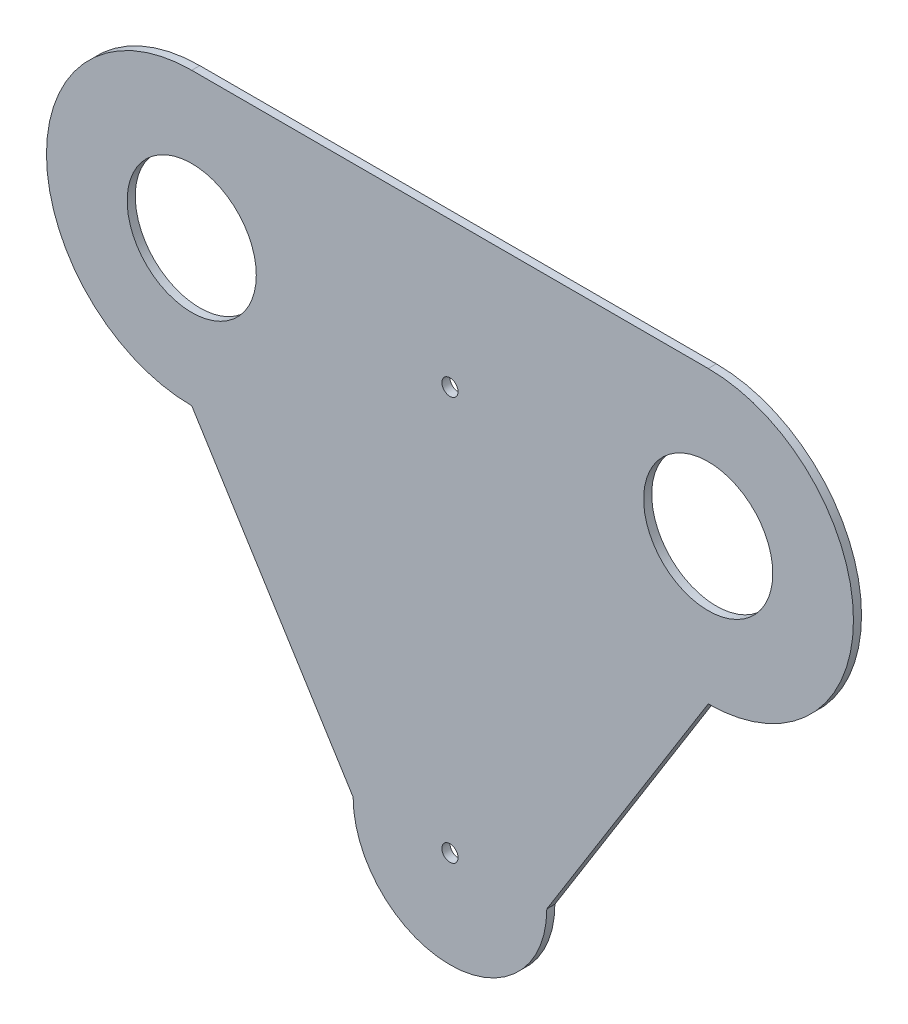
SolidWorks part; units mm, degrees
ref_plane "Front Plane" through (0, 0, 0) normal (0, 0, 1) x (1, 0, 0)
ref_plane "Top Plane" through (0, 0, 0) normal (0, 1, 0) x (1, 0, 0)
ref_plane "Right Plane" through (0, 0, 0) normal (1, 0, 0) x (0, 0, -1)
sketch "Sketch1" plane through (0, 0, 0) normal (0, 0, 1) x (1, 0, 0)
  line L0 (-80, 0) -> (80, 0)
  line L1 (0, 0) -> (0, -125)
  line L2 (-80, 45) -> (80, 45)
  line L3 (-80, -45) -> (-30, -125)
  line L4 (30, -125) -> (80, -45)
  line L5 (-30, -125) -> (30, -125)
  line L6 (-80, -45) -> (80, -45)
  circle A0 centre (-80, 0) radius 20
  circle A1 centre (80, 0) radius 20
  circle A2 centre (0, 0) radius 2.5
  circle A3 centre (0, -125) radius 2.5
  arc A5 (-80, -45) -> (-80, 45) centre (-80, 0) cw
  arc A6 (80, -45) -> (80, 45) centre (80, 0) ccw
  arc A8 (-30, -125) -> (30, -125) centre (0, -125) ccw
  point P4 (0, 0)
  dimension "D1" = 40
  dimension "D2" = 40
  dimension "D4" = 5
  dimension "D6" = 5
  dimension "D7" = 45
  dimension "D8" = 30
  dimension "D5" = 125
  dimension "D3" = 160
extrude "Boss-Extrude1" add sketch "Sketch1" along normal blind 2.5
equation "\"cf_tube_outer_diameter\" = 25mm"
equation "\"cf_tube_inner_diameter\" = 21mm"
equation "\"mid_plate_mid_to_top\" = 100mm"
equation "\"mid_plate_mid_to_bottom\" = 125mm"
equation "\"mid_plate_horizontal_spacing\" = 250mm"
equation "\"mid_tube_length\" = 500mm"
equation "\"D5@Sketch1\"=\"mid_plate_mid_to_bottom\""
equation "\"motor_cutaway_diameter\" = 60mm"
equation "\"mid_plate_motor_cutaway_horizontal_spacing\" = 160mm"
equation "\"D3@Sketch1\"=\"mid_plate_motor_cutaway_horizontal_spacing\""
equation "\"motor_support_diameter\" = 40mm"
equation "\"D1@Sketch1\"=\"motor_support_diameter\""
equation "\"D2@Sketch1\"=\"motor_support_diameter\""
equation "\"D4@Sketch1\"=5mm"
equation "\"D6@Sketch1\"=5mm"
equation "\"D7@Sketch1\"=\"motor_support_diameter\"+5mm"
equation "\"D8@Sketch1\"=\"cf_tube_outer_diameter\"+5mm"
